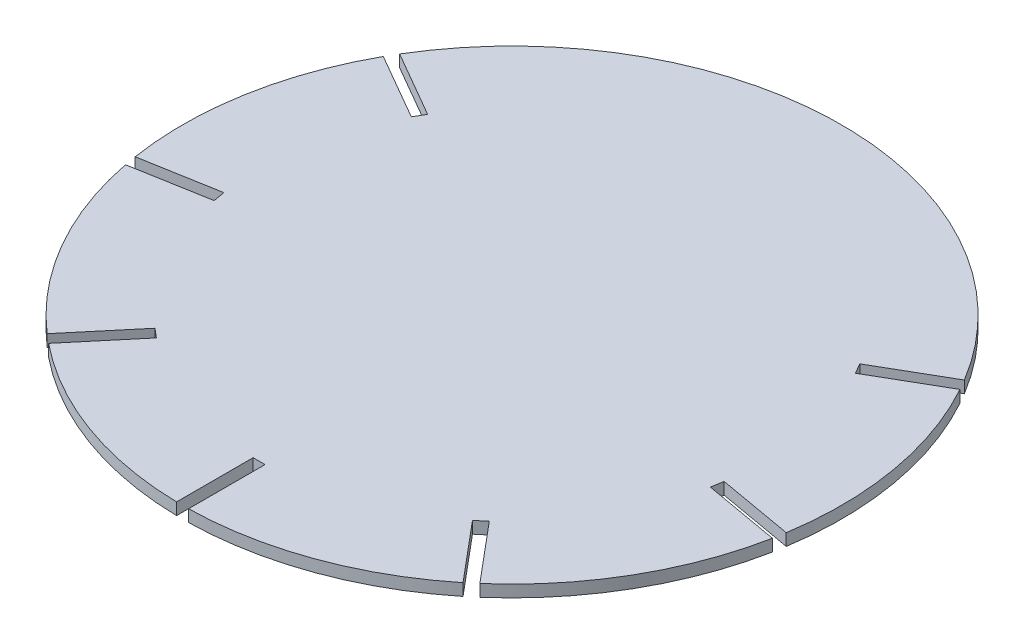
SolidWorks part; units mm, degrees
material "Balsa"
ref_plane "Front Plane" through (0, 0, 0) normal (0, 0, 1) x (1, 0, 0)
ref_plane "Top Plane" through (0, 0, 0) normal (0, 1, 0) x (1, 0, 0)
ref_plane "Right Plane" through (0, 0, 0) normal (1, 0, 0) x (0, 0, -1)
sketch "Sketch1" plane through (0, 0, 0) normal (0, 1, 0) x (1, 0, 0)
  circle A0 centre (0, 0) radius 185
  dimension "D1" = 185
extrude "Boss-Extrude1" add sketch "Sketch1" along normal blind 6.7 contours A0
sketch "Sketch2" plane through (0, 6.7, 0) normal (0, 1, 0) x (1, 0, 0)
  line L0 (0, 0) -> (160.2147, 92.5) construction
  line L2 (121.3006, 73.9012) -> (159.4057, 95.9012)
  line L3 (121.3006, 73.9012) -> (124.6506, 68.0988)
  line L4 (124.6506, 68.0988) -> (162.7557, 90.0988)
  line L5 (159.4057, 95.9012) -> (162.7557, 90.0988)
  line L9 (93.8421, -106.625) -> (122.1247, -140.3309)
  line L10 (93.8421, -106.625) -> (88.7096, -110.9316)
  line L11 (88.7096, -110.9316) -> (116.9922, -144.6376)
  line L12 (122.1247, -140.3309) -> (116.9922, -144.6376)
  line L16 (140.4244, -21.3589) -> (183.756, -28.9995)
  line L17 (140.4244, -21.3589) -> (139.261, -27.9571)
  line L18 (139.261, -27.9571) -> (182.5925, -35.5977)
  line L19 (183.756, -28.9995) -> (182.5925, -35.5977)
  line L23 (0, 0) -> (118.9157, -141.7182) construction
  line L25 (3.35, -142) -> (3.35, -186)
  line L26 (3.35, -142) -> (-3.35, -142)
  line L29 (0, 0) -> (182.1894, -32.1249) construction
  line L30 (-3.35, -142) -> (-3.35, -186)
  line L31 (3.35, -186) -> (-3.35, -186)
  line L34 (0, 0) -> (0, -185) construction
  line L36 (-88.7096, -110.9316) -> (-116.9922, -144.6376)
  line L37 (-88.7096, -110.9316) -> (-93.8421, -106.625)
  line L38 (-93.8421, -106.625) -> (-122.1247, -140.3309)
  line L39 (-116.9922, -144.6376) -> (-122.1247, -140.3309)
  line L42 (0, 0) -> (-118.9157, -141.7182) construction
  line L44 (-139.261, -27.9571) -> (-182.5925, -35.5977)
  line L45 (-139.261, -27.9571) -> (-140.4244, -21.3589)
  line L46 (-140.4244, -21.3589) -> (-183.756, -28.9995)
  line L47 (-182.5925, -35.5977) -> (-183.756, -28.9995)
  line L50 (0, 0) -> (-182.1894, -32.1249) construction
  line L55 (-124.6506, 68.0988) -> (-162.7557, 90.0988)
  line L56 (-124.6506, 68.0988) -> (-121.3006, 73.9012)
  line L57 (-121.3006, 73.9012) -> (-159.4057, 95.9012)
  line L58 (-162.7557, 90.0988) -> (-159.4057, 95.9012)
  line L61 (0, 0) -> (-160.2147, 92.5) construction
  line L63 (0, 0) -> (0, 102.8222) construction
  circle A0 centre (0, 0) radius 185 construction
  point P13 (-12.0777, 27.2748)
  point P75 (122.9756, 71)
  dimension "D1" = 44
  dimension "D2" = 6.7
  dimension "D3" = 3.35
  dimension "D6" = 40
  dimension "D4" = 142
  dimension "D7" = 7
extrude "Cut-Extrude3" cut sketch "Sketch2" against normal blind 6.7
equation "\"Ring inner radius\"= 80mm"
equation "\"D1@Sketch1\"= \"BottomRingCover radius\""
equation "\"Heart cable hole radius\"= 3.5mm"
equation "\"Dogbone radius\"= 3mm"
equation "\"Tree side stock thickness\"= 6.7mm"
equation "\"D2@Sketch2\"= \"Tree side stock thickness\""
equation "\"D3@Sketch2\"= \"Tree side stock thickness\" / 2"
equation "\"Ring stock thickness\"= 6.7mm"
equation "\"D1@Boss-Extrude1\"= \"Ring stock thickness\""
equation "\"Tree teeth\"= 15mm"
equation "\"Tree slot\"= 15mm"
equation "\"D1@Sketch2\"= \"BottomRing inner slot\" + \"Cut-Extrude Tolerance\" + \"Dogbone radius\""
equation "\"Bottom ring outer radius\"= \"Ring inner radius\" + \"Tree teeth\""
equation "\"Cut-Extrude Tolerance\"= 1mm"
equation "\"Ring outer radius\"= \"Ring inner radius\" + \"Tree slot\" + 10"
equation "\"Tree bottom teeth\"= 20mm"
equation "\"Top-bottom rings offset\"= 80mm"
equation "\"BottomRing layers overlap\"= 10mm"
equation "\"BottomRing inner radius\"= \"Bottom reference radius\" + 20"
equation "\"BottomRing outer radius\"= \"BottomRing inner radius\" + \"BottomRing inner slot\" + \"BottomRing outer slot\" + \"BottomRing intersection\""
equation "\"BottomRing inner slot\"= 40mm"
equation "\"BottomRing outer slot\"= 40mm"
equation "\"BottomRing intersection\"= 60mm"
equation "\"BottomRing intersection with dogbones\"= \"BottomRing intersection\" - 2 * \"Dogbone radius\""
equation "\"Bottom reference radius\"= \"Ring inner radius\" - \"Tree teeth\" + \"Top-bottom rings offset\""
equation "\"BottomRingCover radius\"= \"Bottom reference radius\" + \"BottomRing inner slot\""
